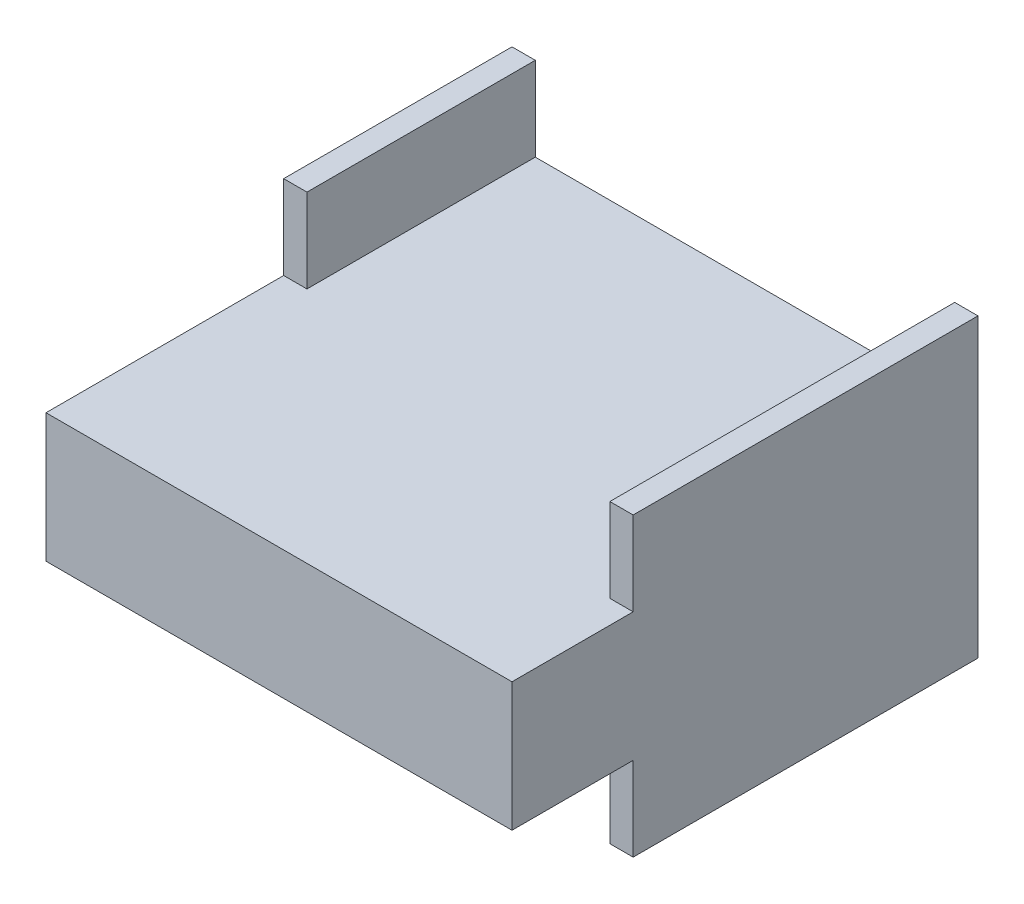
SolidWorks part; units mm, degrees
ref_plane "Front" through (0, 0, 0) normal (0, 0, 1) x (1, 0, 0)
ref_plane "Top" through (0, 0, 0) normal (0, 1, 0) x (1, 0, 0)
ref_plane "Right" through (0, 0, 0) normal (1, 0, 0) x (0, 0, -1)
sketch "Sketch1" plane through (0, 0, 0) normal (0, 1, 0) x (1, 0, 0)
  line L1 (-25, 25) -> (25, 25)
  line L2 (-25, 25) -> (-25, -25)
  line L3 (-25, -25) -> (25, -25)
  line L4 (25, 25) -> (25, -25)
  line L5 (-25, 25) -> (25, -25) construction
  line L6 (-25, -25) -> (25, 25) construction
  point P0 (0, 0)
  dimension "D1" = 50
  dimension "D2" = 50
extrude "Boss-Extrude1" add sketch "Sketch1" along normal mid plane 31.8
sketch "Sketch2" plane through (0, 0, 25) normal (0, 0, 1) x (1, 0, 0)
  line L0 (-25, 15.9) -> (25, 15.9) construction
  line L1 (-22.5, 15.9) -> (22.5, 15.9)
  line L2 (-22.5, 15.9) -> (-22.5, 6.9)
  line L3 (-22.5, 6.9) -> (22.5, 6.9)
  line L4 (22.5, 15.9) -> (22.5, 6.9)
  line L5 (25, 15.9) -> (25, -15.9) construction
  line L6 (-25, 15.9) -> (-25, -15.9) construction
  dimension "D1" = 9
  dimension "D2" = 2.5
  dimension "D3" = 2.5
extrude "Cut-Extrude1" cut sketch "Sketch2" against normal through all
sketch "Sketch3" plane through (22.5, 0, 0) normal (-1, 0, 0) x (0, 0, 1)
  line L0 (-25, 6.9) -> (25, 6.9) construction
  line L1 (12, 6.9) -> (25, 6.9)
  line L2 (12, 6.9) -> (12, 15.9)
  line L3 (12, 15.9) -> (25, 15.9)
  line L4 (25, 6.9) -> (25, 15.9)
  dimension "D1" = 13
extrude "Cut-Extrude2" cut sketch "Sketch3" against normal through all
sketch "Sketch4" plane through (-22.5, 0, 0) normal (1, 0, 0) x (0, 0, -1)
  line L0 (25, 6.9) -> (-25, 6.9) construction
  line L1 (-25, 15.9) -> (0.5, 15.9)
  line L2 (-25, 15.9) -> (-25, 6.9)
  line L3 (-25, 6.9) -> (0.5, 6.9)
  line L4 (0.5, 15.9) -> (0.5, 6.9)
  dimension "D1" = 25.5
extrude "Cut-Extrude3" cut sketch "Sketch4" against normal through all
mirror "Mirror1" about plane through (0, 0, 0) normal (0, 1, 0) of "Cut-Extrude2", "Cut-Extrude3", "Cut-Extrude1"
